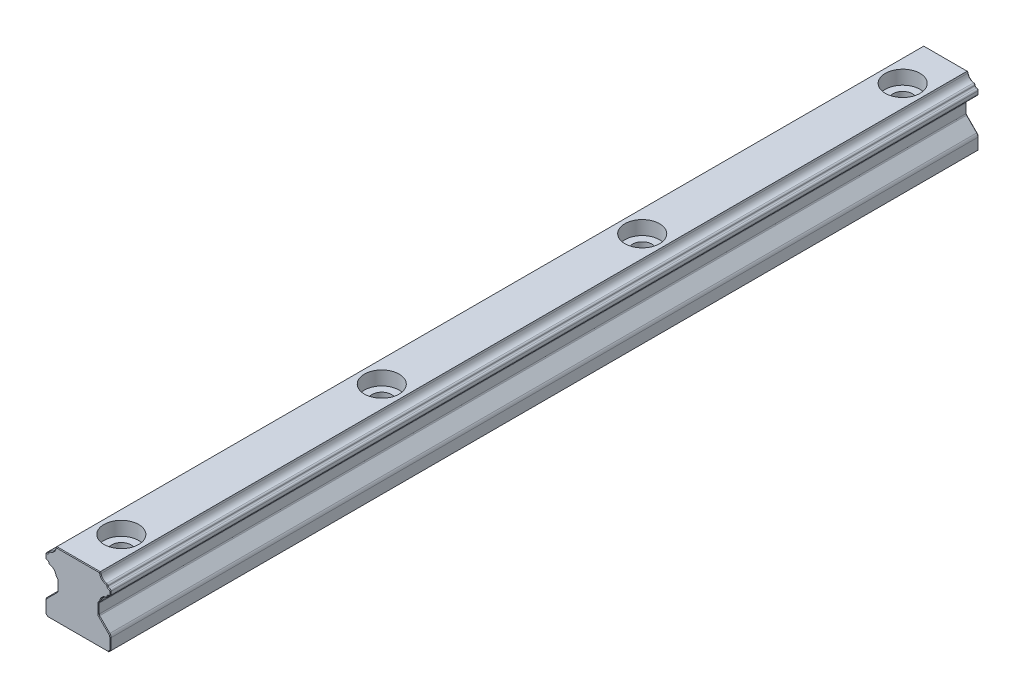
SolidWorks part; units mm, degrees
material "Plain Carbon Steel"
ref_plane "Front Plane" through (0, 0, 0) normal (0, 0, 1) x (1, 0, 0)
ref_plane "Top Plane" through (0, 0, 0) normal (0, 1, 0) x (1, 0, 0)
ref_plane "Right Plane" through (0, 0, 0) normal (1, 0, 0) x (0, 0, -1)
sketch "Rail Profile" plane through (0, 0, 0) normal (0, 0, 1) x (1, 0, 0)
  line L47 (0, 0) -> (0, 20) construction
  line L48 (-7, 0) -> (7, 0)
  line L49 (7, 0) -> (7.5, 0.5)
  line L50 (7.5, 0.5) -> (7.5, 3.0858)
  line L58 (7.2071, 3.7929) -> (4.8672, 6.1328)
  line L59 (4.75, 6.4157) -> (4.75, 8.5843)
  line L60 (4.8672, 8.8672) -> (5.063, 9.063)
  line L61 (7.5, 11.6657) -> (7.5, 12.3343)
  line L62 (-7, 0) -> (-7.5, 0.5)
  line L63 (5, 15) -> (-5, 15)
  line L64 (6.75, 9) -> (6.75, 15) construction
  line L65 (5.063, 14.937) -> (5, 15)
  line L66 (-7.5, 0.5) -> (-7.5, 3.0858)
  line L67 (6.75, 15) -> (3.75, 12) construction
  line L68 (3.75, 12) -> (6.75, 9) construction
  line L69 (7.1, 12.3343) -> (7.1, 11.6657) construction
  line L70 (6.4042, 13.0301) -> (6.4042, 10.9699) construction
  line L71 (-7.2071, 3.7929) -> (-4.8672, 6.1328)
  line L72 (-4.75, 6.4157) -> (-4.75, 8.5843)
  line L73 (-4.8672, 8.8672) -> (-5.063, 9.063)
  line L74 (5, 15) -> (8, 12) construction
  line L75 (4.8672, 8.8672) -> (8, 12) construction
  line L76 (-7.5, 11.6657) -> (-7.5, 12.3343)
  line L77 (-5.063, 14.937) -> (-5, 15)
  arc A4 (6.4734, 13.4241) -> (5.1741, 14.7234) centre (6.75, 15) cw
  arc A6 (5.1741, 9.2766) -> (6.4734, 10.5759) centre (6.75, 9) cw
  arc A7 (7.2071, 3.7929) -> (7.5, 3.0858) centre (6.5, 3.0858) cw
  arc A8 (5.063, 14.937) -> (5.1741, 14.7234) centre (4.7801, 14.6542) cw
  arc A9 (6.4734, 13.4241) -> (6.8012, 13.0792) centre (6.4042, 13.0301) cw
  arc A10 (7.1491, 12.7313) -> (7.5, 12.3343) centre (7.1, 12.3343) cw
  arc A11 (7.5, 11.6657) -> (7.1491, 11.2687) centre (7.1, 11.6657) cw
  arc A12 (6.8012, 10.9208) -> (6.4734, 10.5759) centre (6.4042, 10.9699) cw
  arc A13 (5.1741, 9.2766) -> (5.063, 9.063) centre (4.7801, 9.3458) cw
  arc A14 (4.8672, 8.8672) -> (4.75, 8.5843) centre (5.15, 8.5843) ccw
  arc A15 (4.75, 6.4157) -> (4.8672, 6.1328) centre (5.15, 6.4157) ccw
  arc A16 (6.8012, 13.0792) -> (7.1491, 12.7313) centre (7.1981, 13.1283) ccw
  arc A17 (7.1491, 11.2687) -> (6.8012, 10.9208) centre (7.1981, 10.8717) ccw
  arc A18 (-7.2071, 3.7929) -> (-7.5, 3.0858) centre (-6.5, 3.0858) ccw
  arc A19 (-4.75, 6.4157) -> (-4.8672, 6.1328) centre (-5.15, 6.4157) cw
  arc A20 (-4.8672, 8.8672) -> (-4.75, 8.5843) centre (-5.15, 8.5843) cw
  arc A21 (-5.1741, 9.2766) -> (-5.063, 9.063) centre (-4.7801, 9.3458) ccw
  arc A22 (-5.1741, 9.2766) -> (-6.4734, 10.5759) centre (-6.75, 9) ccw
  arc A23 (-6.8012, 10.9208) -> (-6.4734, 10.5759) centre (-6.4042, 10.9699) ccw
  arc A24 (-7.1491, 11.2687) -> (-6.8012, 10.9208) centre (-7.1981, 10.8717) cw
  arc A25 (-7.5, 11.6657) -> (-7.1491, 11.2687) centre (-7.1, 11.6657) ccw
  arc A26 (-7.1491, 12.7313) -> (-7.5, 12.3343) centre (-7.1, 12.3343) ccw
  arc A27 (-6.8012, 13.0792) -> (-7.1491, 12.7313) centre (-7.1981, 13.1283) cw
  arc A28 (-6.4734, 13.4241) -> (-6.8012, 13.0792) centre (-6.4042, 13.0301) ccw
  arc A29 (-6.4734, 13.4241) -> (-5.1741, 14.7234) centre (-6.75, 15) ccw
  arc A30 (-5.063, 14.937) -> (-5.1741, 14.7234) centre (-4.7801, 14.6542) ccw
  point P2 (4.75, 7.5)
  point P12 (7.5, 12)
  point P19 (6.75, 12)
  point P25 (5.1578, 14.8422)
  point P50 (8, 12)
  point P78 (0, 15)
  dimension "Rb" = 1.6
  dimension "Rf1" = 1
  dimension "Rf2" = 0.4
  dimension "WR" = 15
  dimension "Wi" = 9.5
  dimension "Wt" = 5
  dimension "Ac" = 135
  dimension "HR" = 15
  dimension "Hm" = 7.5
  dimension "Hb" = 12
  dimension "Hc" = 0.5
  dimension "Wb" = 7.5
extrude "Body" add sketch "Rail Profile" against normal blind 200
chamfer "Aesthetic Chamfer" distance 0.15 angle 45 84 edges at (-5.0315, 14.9685, 0) (-5.135, 14.8388, 0) (-5.6186, 13.8686, 0) (-6.6941, 13.3057, 0) (-6.9153, 12.8454, 0) (-7.3997, 12.5992, 0) (-7.5, 12, 0) (-7.3997, 11.4008, 0) (-6.9153, 11.1546, 0) (-6.6941, 10.6943, 0) (-5.6186, 10.1314, 0) (-5.135, 9.1612, 0) (-4.9651, 8.9651, 0) (-4.7804, 8.7374, 0) (-4.75, 7.5, 0) (-4.7804, 6.2626, 0) (-6.0371, 4.9629, 0) (-7.4239, 3.4685, 0) (-7.5, 1.7929, 0) (-7.25, 0.25, 0) (0, 0, 0) (7.25, 0.25, 0) (5.0315, 14.9685, 0) (5.135, 14.8388, 0) (5.6186, 13.8686, 0) (6.6941, 13.3057, 0) (6.9153, 12.8454, 0) (7.3997, 12.5992, 0) (7.5, 12, 0) (7.3997, 11.4008, 0) (6.9153, 11.1546, 0) (6.6941, 10.6943, 0) (5.6186, 10.1314, 0) (5.135, 9.1612, 0) (4.9651, 8.9651, 0) (4.7804, 8.7374, 0) (7.5, 1.7929, 0) (4.75, 7.5, 0) (7.4239, 3.4685, 0) (4.7804, 6.2626, 0) (6.0371, 4.9629, 0) (0, 15, 0) (5.0315, 14.9685, -200) (5.135, 14.8388, -200) (5.6186, 13.8686, -200) (6.6941, 13.3057, -200) (6.9153, 12.8454, -200) (7.3997, 12.5992, -200) (7.5, 12, -200) (7.3997, 11.4008, -200) (6.9153, 11.1546, -200) (6.6941, 10.6943, -200) (5.6186, 10.1314, -200) (5.135, 9.1612, -200) (4.9651, 8.9651, -200) (4.7804, 8.7374, -200) (4.75, 7.5, -200) (4.7804, 6.2626, -200) (6.0371, 4.9629, -200) (7.4239, 3.4685, -200) (7.5, 1.7929, -200) (7.25, 0.25, -200) (0, 0, -200) (-7.25, 0.25, -200) (-5.0315, 14.9685, -200) (-5.135, 14.8388, -200) (-5.6186, 13.8686, -200) (-6.6941, 13.3057, -200) (-6.9153, 12.8454, -200) (-7.3997, 12.5992, -200) (-7.5, 12, -200) (-7.3997, 11.4008, -200) (-6.9153, 11.1546, -200) (-6.6941, 10.6943, -200) (-5.6186, 10.1314, -200) (-7.5, 1.7929, -200) (-5.135, 9.1612, -200) (-7.4239, 3.4685, -200) (-4.9651, 8.9651, -200) (-6.0371, 4.9629, -200) (-4.7804, 8.7374, -200) (-4.7804, 6.2626, -200) (-4.75, 7.5, -200) (0, 15, -200)
sketch "Sketch1" plane through (0, 15, 0) normal (0, 1, 0) x (1, 0, 0)
  point P0 (0, 10)
hole_wizard "CBORE for M4 Hex Socket Head Cap Screw1" positions "Sketch2" profile "Sketch3" counterbore size "M4" standard "DIN" end condition through all
sketch "Sketch2" plane through (0, 15, 0) normal (0, 1, 0) x (1, 0, 0)
  point P0 (0, 10)
sketch "Sketch3" plane through (0, 15, -10) normal (1, 0, 0) x (0, 0, 1)
  line L0 (0, 0) -> (0, 15)
  line L1 (0, 15) -> (2.25, 15)
  line L3 (2.25, 15) -> (2.25, 3.2)
  line L4 (2.25, 3.2) -> (4, 3.2)
  line L5 (4, 3.2) -> (4, 0)
  line L7 (4, 0) -> (0, 0)
  line L11 (0, -6.35) -> (0, 107.95) construction
  dimension "Thru Hole Dia." = 4.5
  dimension "Thru Hole Depth" = 15
  dimension "C'Bore Dia." = 8
  dimension "C'Bore Depth" = 3.2
pattern_linear "LPattern1" count 4 spacing 60 along (0, 0, -1) of "CBORE for M4 Hex Socket Head Cap Screw1"
equation "\"Wt@Rail Profile\"= \"WR@Rail Profile\" / 3'Top Side Half Width"
equation "\"Hm@Rail Profile\"= \"HR@Rail Profile\" / 2'Recirculation Avoidance Height"
equation "\"Hb@Rail Profile\"= 0.8 * \"HR@Rail Profile\"'Pivot Height"
equation "\"Hc@Rail Profile\"= \"WR@Rail Profile\" / 30'Chamfer Width"
equation "\"Wb@Rail Profile\"= \"WR@Rail Profile\" / 2 'Ball Center Cross Width"
